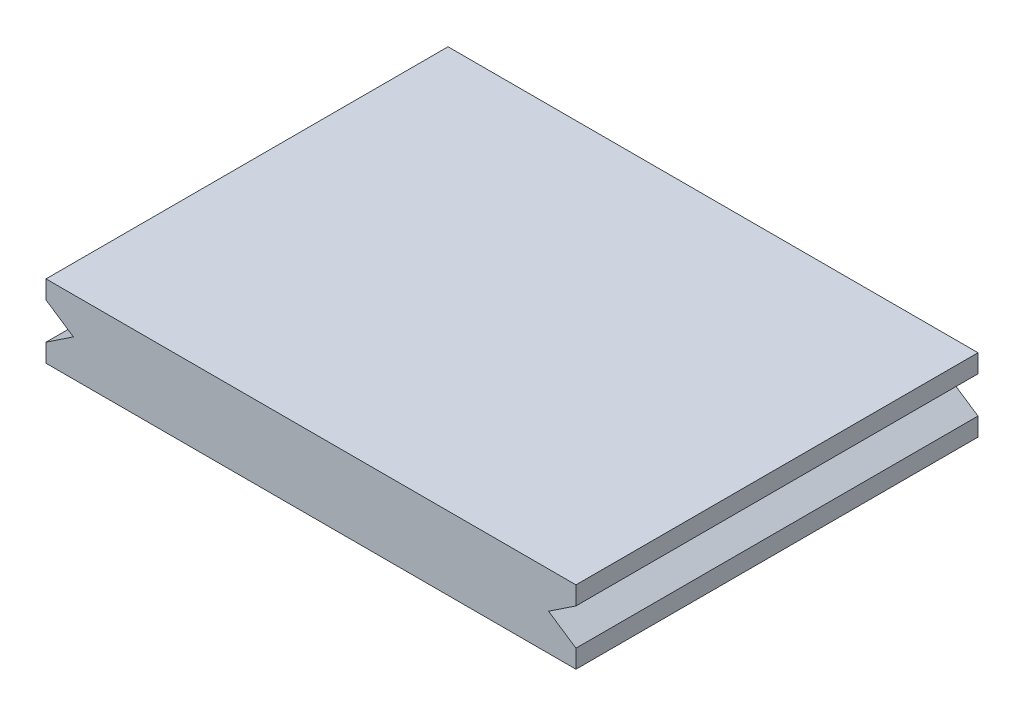
SolidWorks part; units mm, degrees
ref_plane "Přední rovina" through (0, 0, 0) normal (0, 0, 1) x (1, 0, 0)
ref_plane "Horní rovina" through (0, 0, 0) normal (0, 1, 0) x (1, 0, 0)
ref_plane "Pravá rovina" through (0, 0, 0) normal (1, 0, 0) x (0, 0, -1)
sketch "Skica2" plane through (0, 0, 0) normal (0, 0, 1) x (1, 0, 0)
  line L4 (-11.6, -0.8) -> (-10.4, 0)
  line L5 (-11.6, 1.6) -> (11.6, 1.6)
  line L8 (-11.6, 1.6) -> (-11.6, -1.6)
  line L17 (-11.6, -1.6) -> (11.6, -1.6)
  line L18 (11.6, 1.6) -> (11.6, -1.6)
  line L19 (-11.6, 1.6) -> (11.6, -1.6) construction
  line L20 (-11.6, -1.6) -> (11.6, 1.6) construction
  line L21 (-10.4, 0) -> (-11.6, 0.8)
  line L22 (-11.6, 0.8) -> (-11.6, -0.8)
  line L23 (0, 1.6) -> (0, -1.6)
  line L24 (10.4, 0) -> (11.6, 0.8)
  line L25 (11.6, -0.8) -> (10.4, 0)
  line L26 (11.6, 0.8) -> (11.6, -0.8)
  point P0 (0, 0)
  point P12 (0, 0)
  dimension "D1" = 23.2
  dimension "D2" = 3.2
  dimension "D3" = 1.2
  dimension "D4" = 0.8
  dimension "D5" = 0.8
extrude "Přidat vysunutím1" add sketch "Skica2" along normal blind 17.6 contours L18 L25 L24 L5 L23 L17 | L23 L5 L8 L21 L4 L17
